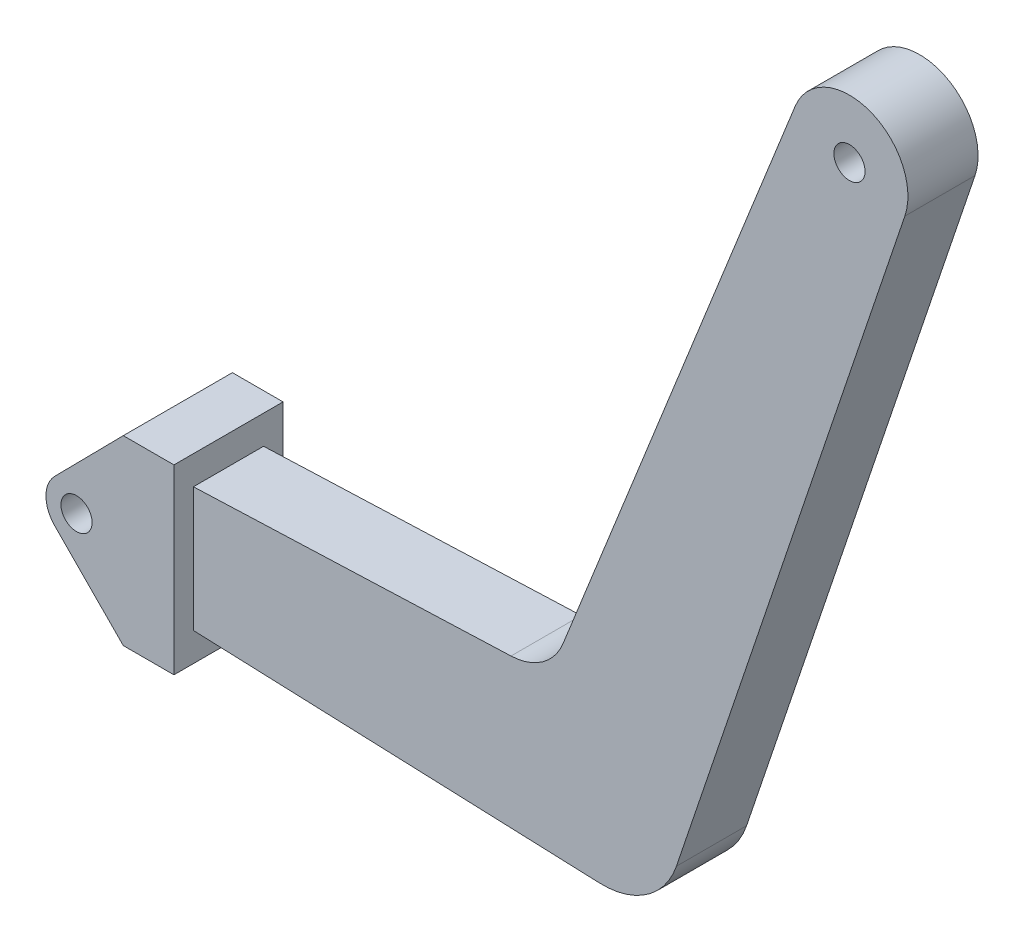
SolidWorks part; units mm, degrees
ref_plane "前视基准面" through (0, 0, 0) normal (0, 0, 1) x (1, 0, 0)
ref_plane "上视基准面" through (0, 0, 0) normal (0, 1, 0) x (1, 0, 0)
ref_plane "右视基准面" through (0, 0, 0) normal (1, 0, 0) x (0, 0, -1)
other "Configuration Table"
sketch "草图1" plane through (0, 0, 0) normal (0, 0, 1) x (1, 0, 0)
  line L0 (0, 0) -> (63.3646, 172.2126) construction
  line L1 (0, 0) -> (-130, 0) construction
  line L28 (-130.5769, 14.9889) -> (-23.4963, 19.1104)
  line L29 (-130, -15) -> (-0.7709, -19.9851)
  line L30 (77.5782, 167.4183) -> (18.951, -6.3923)
  line L35 (49.4333, 177.774) -> (-10.1423, 28.538)
  arc A0 (-0.7709, -19.9851) -> (18.951, -6.3923) centre (0, 0) ccw
  arc A2 (-130.5769, 14.9889) -> (-130, -15) centre (-130, 0) ccw
  arc A3 (77.5782, 167.4183) -> (49.4333, 177.774) centre (63.3646, 172.2126) ccw
  arc A6 (-10.1423, 28.538) -> (-23.4963, 19.1104) centre (-24.0732, 34.0993) cw
  dimension "D1" = 15
extrude "凸台-拉伸1" add sketch "草图1" along normal blind 18
sketch "草图2" plane through (0, 0, 0) normal (0, 0, 1) x (1, 0, 0)
  circle A0 centre (63.3646, 172.2126) radius 4
  circle A1 centre (-130, 0) radius 4
  point P0 (-130, 0)
  point P1 (63.3646, 172.2126)
  point P5 (0, 0)
sketch "草图5" plane through (0, 0, 0) normal (0, 0, 1) x (1, 0, 0)
  line L0 (-130, 0) -> (-130, -15) construction
  line L1 (-130, -15) -> (-0.7709, -19.9851) construction
  line L2 (-130, 0) -> (-130, 15.0111) construction
  line L3 (-23.4963, 19.1104) -> (-130.5769, 14.9889) construction
  point P3 (-130, 15.0111)
ref_plane "基准面5" through (-130, 0, 0) normal (-1, 0, 0) x (0, 0, 1)
sketch "草图10" plane through (-130, 0, 0) normal (-1, 0, 0) x (0, 0, 1)
  line L1 (-18.3922, 24.7758) -> (18.3922, 24.7758)
  line L2 (-18.3922, 24.7758) -> (-18.3922, -24.7758)
  line L3 (-18.3922, -24.7758) -> (18.3922, -24.7758)
  line L4 (18.3922, 24.7758) -> (18.3922, -24.7758)
  line L5 (0, -24.7758) -> (0, 24.7758) construction
  line L6 (-18.3922, 0) -> (18.3922, 0) construction
  point P0 (0, 0)
extrude "切除-拉伸7" cut sketch "草图10" against normal mid plane 50
ref_plane "基准面7" through (-105, 0, 0) normal (-1, 0, 0) x (0, 0, 1)
sketch "草图11" plane through (-105, 0, 0) normal (-1, 0, 0) x (0, 0, 1)
  line L0 (0, 0.0045) -> (9, 0.0045) construction
  line L1 (0, 15.9734) -> (0, -15.9644) construction
  line L3 (-5, 23.3378) -> (23, 23.3378)
  line L4 (-5, 23.3378) -> (-5, -23.3289)
  line L5 (-5, -23.3289) -> (23, -23.3289)
  line L6 (23, 23.3378) -> (23, -23.3289)
  line L7 (9, -23.3289) -> (9, 23.3378) construction
  line L8 (-5, 0.0045) -> (23, 0.0045) construction
  point P7 (0, 0)
extrude "凸台-拉伸2" add sketch "草图11" along normal blind 35
extrude "切除-拉伸9" cut sketch "草图2" against normal mid plane 80
ref_plane "基准面8" through (-140, 0, 0) normal (-1, 0, 0) x (0, 0, 1)
sketch "草图16" plane through (-140, 0, 0) normal (-1, 0, 0) x (0, 0, 1)
  line L1 (1, 0) -> (1, -23.3289)
  line L2 (-5, -23.3289) -> (23, -23.3289) construction
  line L3 (1, -23.3289) -> (17, -23.3289)
  line L4 (17, -23.3289) -> (17, 23.3378)
  line L5 (23, 23.3378) -> (-5, 23.3378) construction
  line L6 (17, 23.3378) -> (1, 23.3378)
  line L7 (1, 23.3378) -> (1, 0)
extrude "切除-拉伸10" cut sketch "草图16" against normal blind 22
sketch "草图17" plane through (0, 0, -5) normal (0, 0, -1) x (-1, 0, 0)
  line L0 (118, 23.3378) -> (140, 23.3378)
  line L1 (118, -23.3378) -> (135.587, -5.5122)
  line L3 (118, 23.3378) -> (135.587, 5.5122)
  line L4 (140, 23.3378) -> (140, -23.3289)
  line L5 (140, -23.3289) -> (118, -23.3378)
  arc A0 (135.587, -5.5122) -> (135.587, 5.5122) centre (130, 0) ccw
extrude "切除-拉伸11" cut sketch "草图17" against normal blind 28
